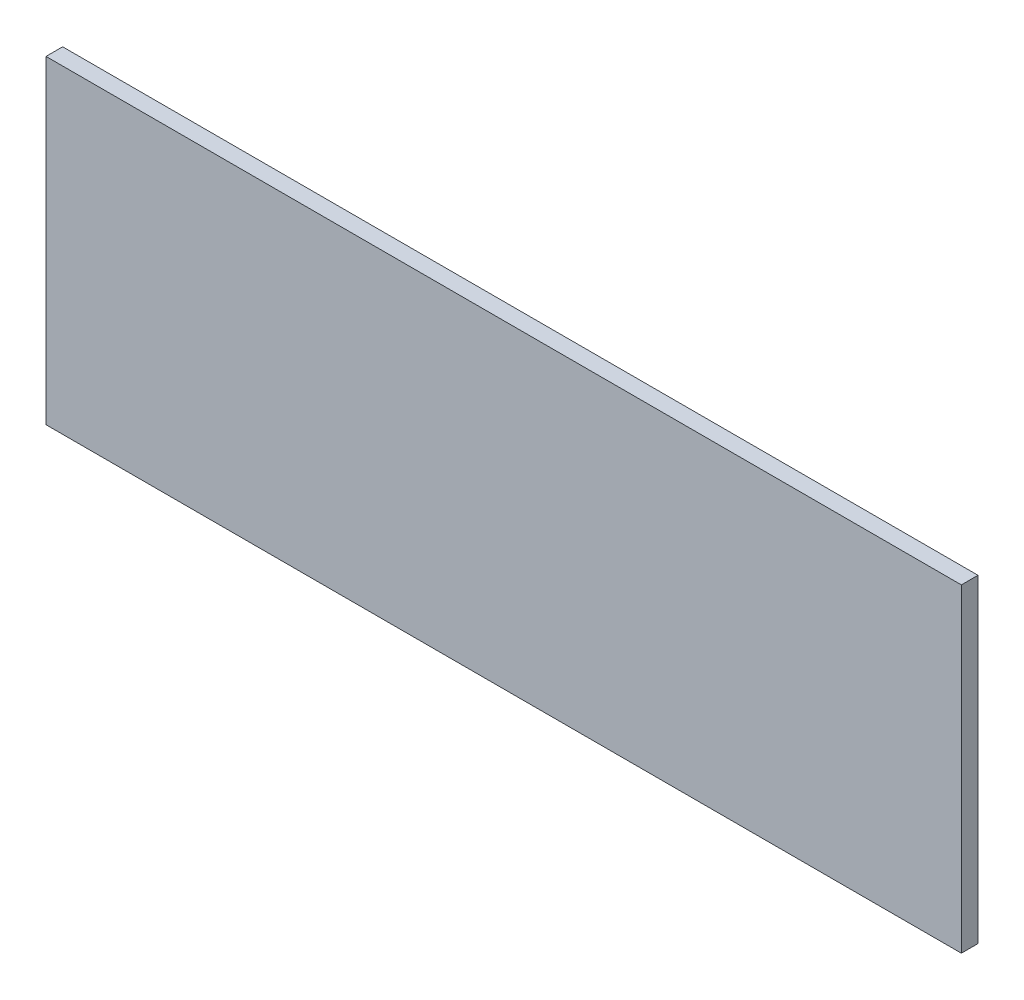
SolidWorks part; units mm, degrees
ref_plane "Plan de face" through (0, 0, 0) normal (0, 0, 1) x (1, 0, 0)
ref_plane "Plan de dessus" through (0, 0, 0) normal (0, 1, 0) x (1, 0, 0)
ref_plane "Plan de droite" through (0, 0, 0) normal (1, 0, 0) x (0, 0, -1)
sketch "Esquisse1" plane through (0, 0, 0) normal (0, 0, 1) x (1, 0, 0)
  line L0 (0, 57.5) -> (0, -57.5) construction
  line L1 (165, -57.5) -> (-165, -57.5)
  line L2 (165, -57.5) -> (165, 57.5)
  line L3 (165, 57.5) -> (-165, 57.5)
  line L4 (-165, -57.5) -> (-165, 57.5)
  line L5 (-165, 0) -> (165, 0) construction
  point P0 (0, 0)
  dimension "D1" = 115
  dimension "D2" = 330
extrude "Boss.-Extru.1" add sketch "Esquisse1" along normal blind 6
